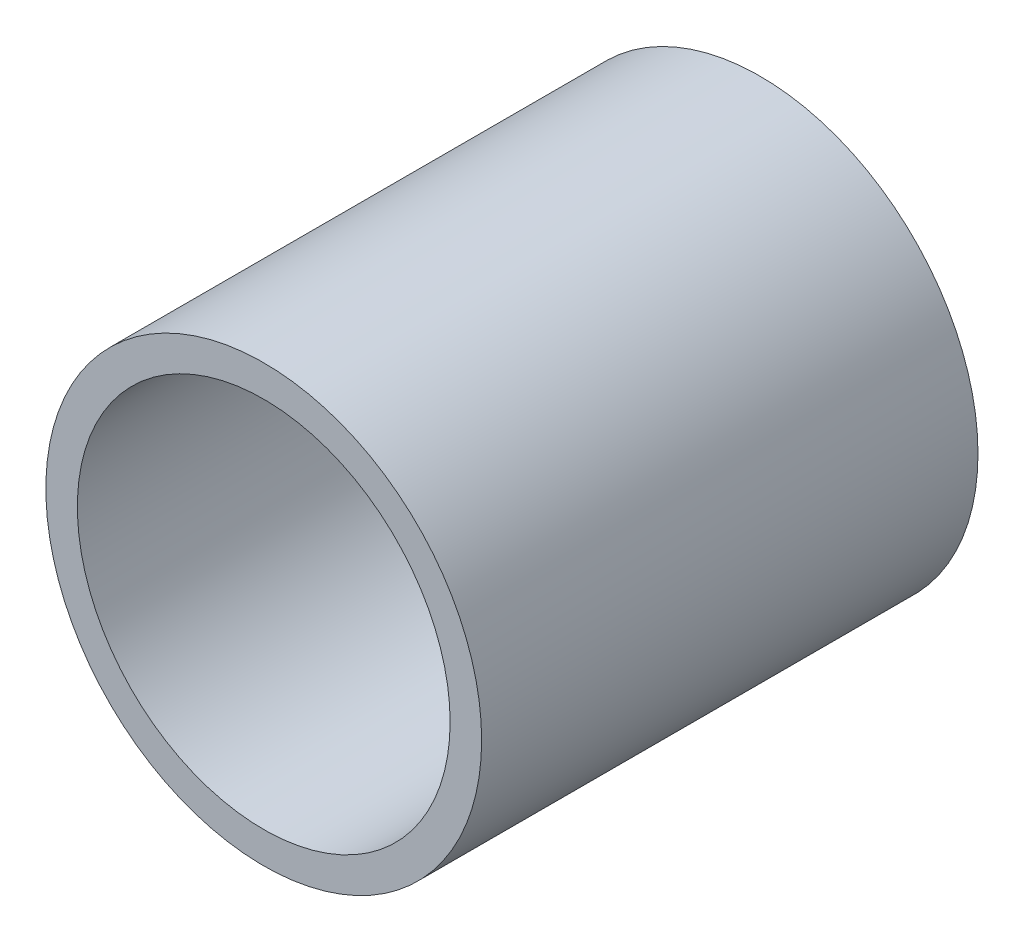
SolidWorks part; units mm, degrees
material "Phosphor bronze 10% D, UNS C52400"
ref_plane "Front Plane" through (0, 0, 0) normal (0, 0, 1) x (1, 0, 0)
ref_plane "Top Plane" through (0, 0, 0) normal (0, 1, 0) x (1, 0, 0)
ref_plane "Right Plane" through (0, 0, 0) normal (1, 0, 0) x (0, 0, -1)
sketch "Sketch1" plane through (0, 0, 0) normal (0, 0, 1) x (1, 0, 0)
  circle A0 centre (0, 0) radius 11.1506
  circle A1 centre (0, 0) radius 9.5377
  dimension "ID" = 19.0754
  dimension "OD" = 22.3012
extrude "Boss-Extrude1" add sketch "Sketch1" along normal mid plane 25.4
sketch "Sketch2" plane through (0, 0, 0) normal (1, 0, 0) x (0, 0, -1)
  line L0 (-12.7, 11.1506) -> (12.7, 11.1506)
  line L1 (-12.7, 0) -> (12.7, 0) construction
  line L2 (-12.7, 11.1506) -> (-12.7, -11.1506) construction
  line L3 (12.7, -11.1506) -> (12.7, 11.1506) construction
  dimension "D1" = 22.3012
  dimension "D2" = 25.4
equation "\"D1@Sketch2\"=\"OD@Sketch1\""
